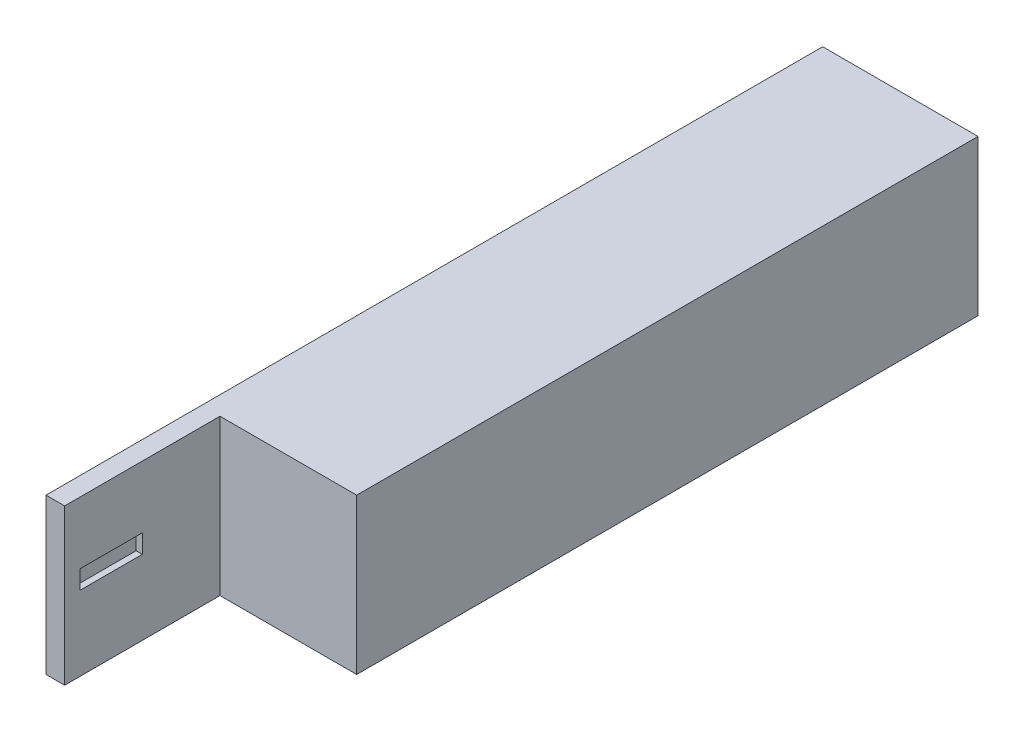
SolidWorks part; units mm, degrees
ref_plane "Front Plane" through (0, 0, 0) normal (0, 0, 1) x (1, 0, 0)
ref_plane "Top Plane" through (0, 0, 0) normal (0, 1, 0) x (1, 0, 0)
ref_plane "Right Plane" through (0, 0, 0) normal (1, 0, 0) x (0, 0, -1)
sketch "Sketch1" plane through (0, 0, 0) normal (0, 0, 1) x (1, 0, 0)
  line L1 (0, 0) -> (50, 0)
  line L2 (0, 0) -> (0, -50)
  line L3 (0, -50) -> (50, -50)
  line L4 (50, 0) -> (50, -50)
  dimension "D1" = 50
  dimension "D2" = 50
extrude "Boss-Extrude1" add sketch "Sketch1" along normal blind 200
sketch "Sketch2" plane through (0, 0, 200) normal (0, 0, 1) x (1, 0, 0)
  line L0 (0, -50) -> (50, -50) construction
  line L1 (0, 0) -> (6, 0)
  line L2 (0, 0) -> (0, -50)
  line L3 (0, -50) -> (6, -50)
  line L4 (6, 0) -> (6, -50)
  dimension "D1" = 6
extrude "Boss-Extrude2" add sketch "Sketch2" along normal blind 50
sketch "Sketch4" plane through (6, 0, 0) normal (1, 0, 0) x (0, 0, -1)
  line L0 (-250, 0) -> (0, 0) construction
  line L1 (-245, -20) -> (-225, -20)
  line L2 (-245, -20) -> (-245, -26)
  line L3 (-245, -26) -> (-225, -26)
  line L4 (-225, -20) -> (-225, -26)
  line L5 (-250, 0) -> (-250, -50) construction
  dimension "D1" = 20
  dimension "D2" = 6
  dimension "D3" = 20
  dimension "D4" = 5
extrude "Cut-Extrude1" cut sketch "Sketch4" against normal blind 2
sketch "Sketch5" plane through (0, 0, 0) normal (0, 0, -1) x (-1, 0, 0)
  line L0 (-25, 0) -> (-25, -50) construction
  line L1 (-50, 0) -> (0, 0) construction
  line L2 (0, -50) -> (-50, -50) construction
  line L3 (-50, -25) -> (0, -25) construction
  line L4 (-36.315, -25) -> (-13.685, -25)
  line L5 (-25, -25) -> (-25, -31.095)
  line L6 (-36.315, -31.095) -> (-13.685, -31.095)
  line L7 (-13.685, -18.905) -> (-13.685, -31.095)
  line L8 (-50, -50) -> (-50, 0) construction
  line L9 (0, 0) -> (0, -50) construction
  line L10 (-36.315, -18.905) -> (-36.315, -31.095)
  line L11 (-36.315, -18.905) -> (-13.685, -18.905)
  dimension "D1" = 11.315
  dimension "D2" = 6.095
extrude "Cut-Extrude2" cut sketch "Sketch5" against normal blind 10.84 contours L11 L10 L4 L7 | L4 L10 L6 L5 | L7 L4 L5 L6
